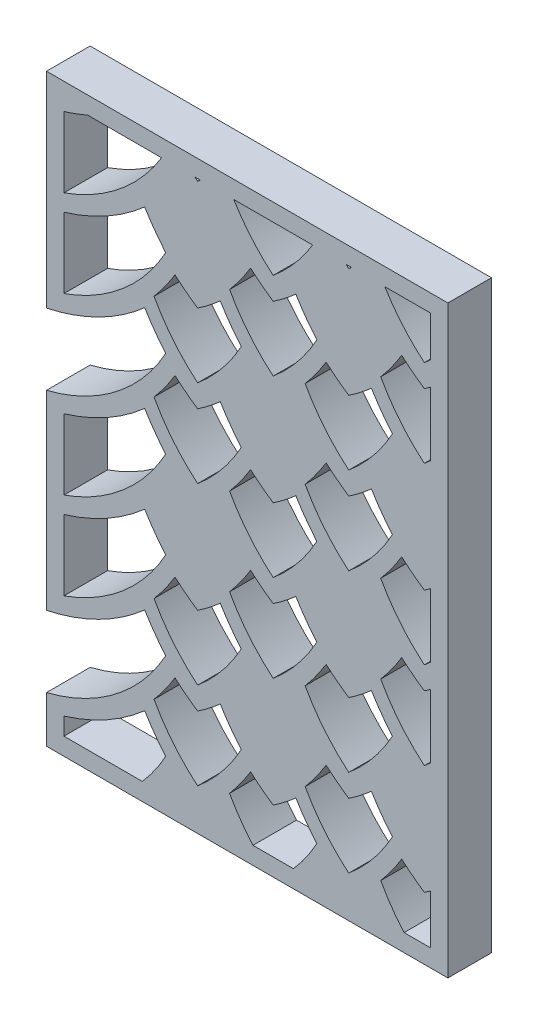
SolidWorks part; units mm, degrees
ref_plane "Front Plane" through (0, 0, 0) normal (0, 0, 1) x (1, 0, 0)
ref_plane "Top Plane" through (0, 0, 0) normal (0, 1, 0) x (1, 0, 0)
ref_plane "Right Plane" through (0, 0, 0) normal (1, 0, 0) x (0, 0, -1)
sketch "Sketch2" plane through (0, 0, 0) normal (0, 0, 1) x (1, 0, 0)
  line L0 (0, -12.607) -> (0, 160.3809) construction
  arc A12 (17.3205, 5.288) -> (12.3204, 11.3793) centre (31.1051, 21.7008) cw
  arc A13 (12.3204, 11.3793) -> (14.7264, 14.712) centre (-6.459, 27.4714) ccw
  arc A14 (17.3205, 12.7089) -> (14.7264, 14.712) centre (31.1051, 33.242) cw
  arc A15 (17.3205, 12.7089) -> (19.9146, 14.712) centre (3.5359, 33.242) ccw
  arc A16 (22.3206, 11.3793) -> (19.9146, 14.712) centre (41.1, 27.4714) cw
  arc A17 (17.3205, 5.288) -> (22.3206, 11.3793) centre (3.5359, 21.7008) ccw
  arc A18 (25.9808, 10.288) -> (20.9807, 16.3793) centre (39.7653, 26.7008) cw
  arc A19 (20.9807, 16.3793) -> (23.3866, 19.712) centre (2.2013, 32.4714) ccw
  arc A20 (25.9808, 17.7089) -> (23.3866, 19.712) centre (39.7653, 38.242) cw
  arc A21 (25.9808, 17.7089) -> (28.5749, 19.712) centre (12.1962, 38.242) ccw
  arc A22 (30.9808, 16.3793) -> (28.5749, 19.712) centre (49.7603, 32.4714) cw
  arc A23 (25.9808, 10.288) -> (30.9808, 16.3793) centre (12.1962, 26.7008) ccw
  arc A30 (43.3013, 20.288) -> (38.3012, 26.3793) centre (57.0859, 36.7008) cw
  arc A31 (38.3012, 26.3793) -> (40.7071, 29.712) centre (19.5218, 42.4714) ccw
  arc A32 (43.3013, 27.7089) -> (40.7071, 29.712) centre (57.0859, 48.242) cw
  arc A33 (43.3013, 27.7089) -> (45.8954, 29.712) centre (29.5167, 48.242) ccw
  arc A34 (48.3013, 26.3793) -> (45.8954, 29.712) centre (67.0808, 42.4714) cw
  arc A35 (43.3013, 20.288) -> (48.3013, 26.3793) centre (29.5167, 36.7008) ccw
  arc A36 (51.9615, 25.288) -> (46.9615, 31.3793) centre (65.7461, 41.7008) cw
  arc A37 (46.9615, 31.3793) -> (49.3674, 34.712) centre (28.182, 47.4714) ccw
  arc A38 (51.9615, 32.7089) -> (49.3674, 34.712) centre (65.7461, 53.242) cw
  arc A39 (51.9615, 32.7089) -> (54.5557, 34.712) centre (38.1769, 53.242) ccw
  arc A40 (56.9616, 31.3793) -> (54.5557, 34.712) centre (75.741, 47.4714) cw
  arc A41 (51.9615, 25.288) -> (56.9616, 31.3793) centre (38.1769, 41.7008) ccw
  arc A60 (25.9808, 20.288) -> (20.9807, 26.3793) centre (39.7653, 36.7008) cw
  arc A61 (20.9807, 26.3793) -> (23.3866, 29.712) centre (2.2013, 42.4714) ccw
  arc A62 (25.9808, 27.7089) -> (23.3866, 29.712) centre (39.7653, 48.242) cw
  arc A63 (25.9808, 27.7089) -> (28.5749, 29.712) centre (12.1962, 48.242) ccw
  arc A64 (30.9808, 26.3793) -> (28.5749, 29.712) centre (49.7603, 42.4714) cw
  arc A65 (25.9808, 20.288) -> (30.9808, 26.3793) centre (12.1962, 36.7008) ccw
  arc A66 (34.641, 25.288) -> (29.641, 31.3793) centre (48.4256, 41.7008) cw
  arc A67 (29.641, 31.3793) -> (32.0469, 34.712) centre (10.8615, 47.4714) ccw
  arc A68 (34.641, 32.7089) -> (32.0469, 34.712) centre (48.4256, 53.242) cw
  arc A69 (34.641, 32.7089) -> (37.2351, 34.712) centre (20.8564, 53.242) ccw
  arc A70 (39.6411, 31.3793) -> (37.2351, 34.712) centre (58.4205, 47.4714) cw
  arc A71 (34.641, 25.288) -> (39.6411, 31.3793) centre (20.8564, 41.7008) ccw
  arc A78 (51.9615, 35.288) -> (46.9615, 41.3793) centre (65.7461, 51.7008) cw
  arc A79 (46.9615, 41.3793) -> (49.3674, 44.712) centre (28.182, 57.4714) ccw
  arc A80 (51.9615, 42.7089) -> (49.3674, 44.712) centre (65.7461, 63.242) cw
  arc A81 (51.9615, 42.7089) -> (54.5557, 44.712) centre (38.1769, 63.242) ccw
  arc A82 (56.9616, 41.3793) -> (54.5557, 44.712) centre (75.741, 57.4714) cw
  arc A83 (51.9615, 35.288) -> (56.9616, 41.3793) centre (38.1769, 51.7008) ccw
  arc A84 (60.6218, 40.288) -> (55.6217, 46.3793) centre (74.4064, 56.7008) cw
  arc A85 (55.6217, 46.3793) -> (58.0276, 49.712) centre (36.8423, 62.4714) ccw
  arc A86 (60.6218, 47.7089) -> (58.0276, 49.712) centre (74.4064, 68.242) cw
  arc A87 (60.6218, 47.7089) -> (63.2159, 49.712) centre (46.8372, 68.242) ccw
  arc A88 (65.6218, 46.3793) -> (63.2159, 49.712) centre (84.4013, 62.4714) cw
  arc A89 (60.6218, 40.288) -> (65.6218, 46.3793) centre (46.8372, 56.7008) ccw
  arc A96 (17.3205, 25.288) -> (12.3204, 31.3793) centre (31.1051, 41.7008) cw
  arc A97 (12.3204, 31.3793) -> (14.7264, 34.712) centre (-6.459, 47.4714) ccw
  arc A98 (17.3205, 32.7089) -> (14.7264, 34.712) centre (31.1051, 53.242) cw
  arc A99 (17.3205, 32.7089) -> (19.9146, 34.712) centre (3.5359, 53.242) ccw
  arc A100 (22.3206, 31.3793) -> (19.9146, 34.712) centre (41.1, 47.4714) cw
  arc A101 (17.3205, 25.288) -> (22.3206, 31.3793) centre (3.5359, 41.7008) ccw
  arc A108 (34.641, 35.288) -> (29.641, 41.3793) centre (48.4256, 51.7008) cw
  arc A109 (29.641, 41.3793) -> (32.0469, 44.712) centre (10.8615, 57.4714) ccw
  arc A110 (34.641, 42.7089) -> (32.0469, 44.712) centre (48.4256, 63.242) cw
  arc A111 (34.641, 42.7089) -> (37.2351, 44.712) centre (20.8564, 63.242) ccw
  arc A112 (39.6411, 41.3793) -> (37.2351, 44.712) centre (58.4205, 57.4714) cw
  arc A113 (34.641, 35.288) -> (39.6411, 41.3793) centre (20.8564, 51.7008) ccw
  arc A114 (43.3013, 40.288) -> (38.3012, 46.3793) centre (57.0859, 56.7008) cw
  arc A115 (38.3012, 46.3793) -> (40.7071, 49.712) centre (19.5218, 62.4714) ccw
  arc A116 (43.3013, 47.7089) -> (40.7071, 49.712) centre (57.0859, 68.242) cw
  arc A117 (43.3013, 47.7089) -> (45.8954, 49.712) centre (29.5167, 68.242) ccw
  arc A118 (48.3013, 46.3793) -> (45.8954, 49.712) centre (67.0808, 62.4714) cw
  arc A119 (43.3013, 40.288) -> (48.3013, 46.3793) centre (29.5167, 56.7008) ccw
  arc A126 (60.6218, 50.288) -> (55.6217, 56.3793) centre (74.4064, 66.7008) cw
  arc A127 (55.6217, 56.3793) -> (58.0276, 59.712) centre (36.8423, 72.4714) ccw
  arc A128 (60.6218, 57.7089) -> (58.0276, 59.712) centre (74.4064, 78.242) cw
  arc A129 (60.6218, 57.7089) -> (63.2159, 59.712) centre (46.8372, 78.242) ccw
  arc A130 (65.6218, 56.3793) -> (63.2159, 59.712) centre (84.4013, 72.4714) cw
  arc A131 (60.6218, 50.288) -> (65.6218, 56.3793) centre (46.8372, 66.7008) ccw
  arc A138 (17.3205, 35.288) -> (12.3204, 41.3793) centre (31.1051, 51.7008) cw
  arc A139 (12.3204, 41.3793) -> (14.7264, 44.712) centre (-6.459, 57.4714) ccw
  arc A140 (17.3205, 42.7089) -> (14.7264, 44.712) centre (31.1051, 63.242) cw
  arc A141 (17.3205, 42.7089) -> (19.9146, 44.712) centre (3.5359, 63.242) ccw
  arc A142 (22.3206, 41.3793) -> (19.9146, 44.712) centre (41.1, 57.4714) cw
  arc A143 (17.3205, 35.288) -> (22.3206, 41.3793) centre (3.5359, 51.7008) ccw
  arc A144 (25.9808, 40.288) -> (20.9807, 46.3793) centre (39.7653, 56.7008) cw
  arc A145 (20.9807, 46.3793) -> (23.3866, 49.712) centre (2.2013, 62.4714) ccw
  arc A146 (25.9808, 47.7089) -> (23.3866, 49.712) centre (39.7653, 68.242) cw
  arc A147 (25.9808, 47.7089) -> (28.5749, 49.712) centre (12.1962, 68.242) ccw
  arc A148 (30.9808, 46.3793) -> (28.5749, 49.712) centre (49.7603, 62.4714) cw
  arc A149 (25.9808, 40.288) -> (30.9808, 46.3793) centre (12.1962, 56.7008) ccw
  arc A156 (43.3013, 50.288) -> (38.3012, 56.3793) centre (57.0859, 66.7008) cw
  arc A157 (38.3012, 56.3793) -> (40.7071, 59.712) centre (19.5218, 72.4714) ccw
  arc A158 (43.3013, 57.7089) -> (40.7071, 59.712) centre (57.0859, 78.242) cw
  arc A159 (43.3013, 57.7089) -> (45.8954, 59.712) centre (29.5167, 78.242) ccw
  arc A160 (48.3013, 56.3793) -> (45.8954, 59.712) centre (67.0808, 72.4714) cw
  arc A161 (43.3013, 50.288) -> (48.3013, 56.3793) centre (29.5167, 66.7008) ccw
  arc A162 (51.9615, 55.288) -> (46.9615, 61.3793) centre (65.7461, 71.7008) cw
  arc A163 (46.9615, 61.3793) -> (49.3674, 64.712) centre (28.182, 77.4714) ccw
  arc A164 (51.9615, 62.7089) -> (49.3674, 64.712) centre (65.7461, 83.242) cw
  arc A165 (51.9615, 62.7089) -> (54.5557, 64.712) centre (38.1769, 83.242) ccw
  arc A166 (56.9616, 61.3793) -> (54.5557, 64.712) centre (75.741, 77.4714) cw
  arc A167 (51.9615, 55.288) -> (56.9616, 61.3793) centre (38.1769, 71.7008) ccw
  arc A186 (25.9808, 50.288) -> (20.9807, 56.3793) centre (39.7653, 66.7008) cw
  arc A187 (20.9807, 56.3793) -> (23.3866, 59.712) centre (2.2013, 72.4714) ccw
  arc A188 (25.9808, 57.7089) -> (23.3866, 59.712) centre (39.7653, 78.242) cw
  arc A189 (25.9808, 57.7089) -> (28.5749, 59.712) centre (12.1962, 78.242) ccw
  arc A190 (30.9808, 56.3793) -> (28.5749, 59.712) centre (49.7603, 72.4714) cw
  arc A191 (25.9808, 50.288) -> (30.9808, 56.3793) centre (12.1962, 66.7008) ccw
  arc A192 (34.641, 55.288) -> (29.641, 61.3793) centre (48.4256, 71.7008) cw
  arc A193 (29.641, 61.3793) -> (32.0469, 64.712) centre (10.8615, 77.4714) ccw
  arc A194 (34.641, 62.7089) -> (32.0469, 64.712) centre (48.4256, 83.242) cw
  arc A195 (34.641, 62.7089) -> (37.2351, 64.712) centre (20.8564, 83.242) ccw
  arc A196 (39.6411, 61.3793) -> (37.2351, 64.712) centre (58.4205, 77.4714) cw
  arc A197 (34.641, 55.288) -> (39.6411, 61.3793) centre (20.8564, 71.7008) ccw
  arc A204 (51.9615, 65.288) -> (46.9615, 71.3793) centre (65.7461, 81.7008) cw
  arc A205 (46.9615, 71.3793) -> (49.3674, 74.712) centre (28.182, 87.4714) ccw
  arc A206 (51.9615, 72.7089) -> (49.3674, 74.712) centre (65.7461, 93.242) cw
  arc A207 (51.9615, 72.7089) -> (54.5557, 74.712) centre (38.1769, 93.242) ccw
  arc A208 (56.9616, 71.3793) -> (54.5557, 74.712) centre (75.741, 87.4714) cw
  arc A209 (51.9615, 65.288) -> (56.9616, 71.3793) centre (38.1769, 81.7008) ccw
  arc A210 (60.6218, 70.288) -> (55.6217, 76.3793) centre (74.4064, 86.7008) cw
  arc A211 (55.6217, 76.3793) -> (58.0276, 79.712) centre (36.8423, 92.4714) ccw
  arc A212 (60.6218, 77.7089) -> (58.0276, 79.712) centre (74.4064, 98.242) cw
  arc A213 (60.6218, 77.7089) -> (63.2159, 79.712) centre (46.8372, 98.242) ccw
  arc A214 (65.6218, 76.3793) -> (63.2159, 79.712) centre (84.4013, 92.4714) cw
  arc A215 (60.6218, 70.288) -> (65.6218, 76.3793) centre (46.8372, 86.7008) ccw
  arc A222 (17.3205, 55.288) -> (12.3204, 61.3793) centre (31.1051, 71.7008) cw
  arc A223 (12.3204, 61.3793) -> (14.7264, 64.712) centre (-6.459, 77.4714) ccw
  arc A224 (17.3205, 62.7089) -> (14.7264, 64.712) centre (31.1051, 83.242) cw
  arc A225 (17.3205, 62.7089) -> (19.9146, 64.712) centre (3.5359, 83.242) ccw
  arc A226 (22.3206, 61.3793) -> (19.9146, 64.712) centre (41.1, 77.4714) cw
  arc A227 (17.3205, 55.288) -> (22.3206, 61.3793) centre (3.5359, 71.7008) ccw
  arc A234 (34.641, 65.288) -> (29.641, 71.3793) centre (48.4256, 81.7008) cw
  arc A235 (29.641, 71.3793) -> (32.0469, 74.712) centre (10.8615, 87.4714) ccw
  arc A236 (34.641, 72.7089) -> (32.0469, 74.712) centre (48.4256, 93.242) cw
  arc A237 (34.641, 72.7089) -> (37.2351, 74.712) centre (20.8564, 93.242) ccw
  arc A238 (39.6411, 71.3793) -> (37.2351, 74.712) centre (58.4205, 87.4714) cw
  arc A239 (34.641, 65.288) -> (39.6411, 71.3793) centre (20.8564, 81.7008) ccw
  arc A240 (43.3013, 70.288) -> (38.3012, 76.3793) centre (57.0859, 86.7008) cw
  arc A241 (38.3012, 76.3793) -> (40.7071, 79.712) centre (19.5218, 92.4714) ccw
  arc A242 (43.3013, 77.7089) -> (40.7071, 79.712) centre (57.0859, 98.242) cw
  arc A243 (43.3013, 77.7089) -> (45.8954, 79.712) centre (29.5167, 98.242) ccw
  arc A244 (48.3013, 76.3793) -> (45.8954, 79.712) centre (67.0808, 92.4714) cw
  arc A245 (43.3013, 70.288) -> (48.3013, 76.3793) centre (29.5167, 86.7008) ccw
  arc A252 (60.6218, 80.288) -> (55.6217, 86.3793) centre (74.4064, 96.7008) cw
  arc A253 (55.6217, 86.3793) -> (58.0276, 89.712) centre (36.8423, 102.4714) ccw
  arc A254 (60.6218, 87.7089) -> (58.0276, 89.712) centre (74.4064, 108.242) cw
  arc A255 (60.6218, 87.7089) -> (63.2159, 89.712) centre (46.8372, 108.242) ccw
  arc A256 (65.6218, 86.3793) -> (63.2159, 89.712) centre (84.4013, 102.4714) cw
  arc A257 (60.6218, 80.288) -> (65.6218, 86.3793) centre (46.8372, 96.7008) ccw
  arc A264 (17.3205, 65.288) -> (12.3204, 71.3793) centre (31.1051, 81.7008) cw
  arc A265 (12.3204, 71.3793) -> (14.7264, 74.712) centre (-6.459, 87.4714) ccw
  arc A266 (17.3205, 72.7089) -> (14.7264, 74.712) centre (31.1051, 93.242) cw
  arc A267 (17.3205, 72.7089) -> (19.9146, 74.712) centre (3.5359, 93.242) ccw
  arc A268 (22.3206, 71.3793) -> (19.9146, 74.712) centre (41.1, 87.4714) cw
  arc A269 (17.3205, 65.288) -> (22.3206, 71.3793) centre (3.5359, 81.7008) ccw
  arc A270 (25.9808, 70.288) -> (20.9807, 76.3793) centre (39.7653, 86.7008) cw
  arc A271 (20.9807, 76.3793) -> (23.3866, 79.712) centre (2.2013, 92.4714) ccw
  arc A272 (25.9808, 77.7089) -> (23.3866, 79.712) centre (39.7653, 98.242) cw
  arc A273 (25.9808, 77.7089) -> (28.5749, 79.712) centre (12.1962, 98.242) ccw
  arc A274 (30.9808, 76.3793) -> (28.5749, 79.712) centre (49.7603, 92.4714) cw
  arc A275 (25.9808, 70.288) -> (30.9808, 76.3793) centre (12.1962, 86.7008) ccw
  arc A282 (43.3013, 80.288) -> (38.3012, 86.3793) centre (57.0859, 96.7008) cw
  arc A283 (38.3012, 86.3793) -> (40.7071, 89.712) centre (19.5218, 102.4714) ccw
  arc A284 (43.3013, 87.7089) -> (40.7071, 89.712) centre (57.0859, 108.242) cw
  arc A285 (43.3013, 87.7089) -> (45.8954, 89.712) centre (29.5167, 108.242) ccw
  arc A286 (48.3013, 86.3793) -> (45.8954, 89.712) centre (67.0808, 102.4714) cw
  arc A287 (43.3013, 80.288) -> (48.3013, 86.3793) centre (29.5167, 96.7008) ccw
  arc A288 (51.9615, 85.288) -> (46.9615, 91.3793) centre (65.7461, 101.7008) cw
  arc A289 (46.9615, 91.3793) -> (49.3674, 94.712) centre (28.182, 107.4714) ccw
  arc A290 (51.9615, 92.7089) -> (49.3674, 94.712) centre (65.7461, 113.242) cw
  arc A291 (51.9615, 92.7089) -> (54.5557, 94.712) centre (38.1769, 113.242) ccw
  arc A292 (56.9616, 91.3793) -> (54.5557, 94.712) centre (75.741, 107.4714) cw
  arc A293 (51.9615, 85.288) -> (56.9616, 91.3793) centre (38.1769, 101.7008) ccw
  arc A312 (25.9808, 80.288) -> (20.9807, 86.3793) centre (39.7653, 96.7008) cw
  arc A313 (20.9807, 86.3793) -> (23.3866, 89.712) centre (2.2013, 102.4714) ccw
  arc A314 (25.9808, 87.7089) -> (23.3866, 89.712) centre (39.7653, 108.242) cw
  arc A315 (25.9808, 87.7089) -> (28.5749, 89.712) centre (12.1962, 108.242) ccw
  arc A316 (30.9808, 86.3793) -> (28.5749, 89.712) centre (49.7603, 102.4714) cw
  arc A317 (25.9808, 80.288) -> (30.9808, 86.3793) centre (12.1962, 96.7008) ccw
  arc A318 (34.641, 85.288) -> (29.641, 91.3793) centre (48.4256, 101.7008) cw
  arc A319 (29.641, 91.3793) -> (32.0469, 94.712) centre (10.8615, 107.4714) ccw
  arc A320 (34.641, 92.7089) -> (32.0469, 94.712) centre (48.4256, 113.242) cw
  arc A321 (34.641, 92.7089) -> (37.2351, 94.712) centre (20.8564, 113.242) ccw
  arc A322 (39.6411, 91.3793) -> (37.2351, 94.712) centre (58.4205, 107.4714) cw
  arc A323 (34.641, 85.288) -> (39.6411, 91.3793) centre (20.8564, 101.7008) ccw
  arc A330 (51.9615, 95.288) -> (46.9615, 101.3793) centre (65.7461, 111.7008) cw
  arc A331 (46.9615, 101.3793) -> (49.3674, 104.712) centre (28.182, 117.4714) ccw
  arc A332 (51.9615, 102.7089) -> (49.3674, 104.712) centre (65.7461, 123.242) cw
  arc A333 (51.9615, 102.7089) -> (54.5557, 104.712) centre (38.1769, 123.242) ccw
  arc A334 (56.9616, 101.3793) -> (54.5557, 104.712) centre (75.741, 117.4714) cw
  arc A335 (51.9615, 95.288) -> (56.9616, 101.3793) centre (38.1769, 111.7008) ccw
  arc A336 (60.6218, 100.288) -> (55.6217, 106.3793) centre (74.4064, 116.7008) cw
  arc A337 (55.6217, 106.3793) -> (58.0276, 109.712) centre (36.8423, 122.4714) ccw
  arc A338 (60.6218, 107.7089) -> (58.0276, 109.712) centre (74.4064, 128.242) cw
  arc A339 (60.6218, 107.7089) -> (63.2159, 109.712) centre (46.8372, 128.242) ccw
  arc A340 (65.6218, 106.3793) -> (63.2159, 109.712) centre (84.4013, 122.4714) cw
  arc A341 (60.6218, 100.288) -> (65.6218, 106.3793) centre (46.8372, 116.7008) ccw
  arc A396 (17.3205, 85.288) -> (12.3204, 91.3793) centre (31.1051, 101.7008) cw
  arc A397 (12.3204, 91.3793) -> (14.7264, 94.712) centre (-6.459, 107.4714) ccw
  arc A398 (17.3205, 92.7089) -> (14.7264, 94.712) centre (31.1051, 113.242) cw
  arc A399 (17.3205, 92.7089) -> (19.9146, 94.712) centre (3.5359, 113.242) ccw
  arc A400 (22.3206, 91.3793) -> (19.9146, 94.712) centre (41.1, 107.4714) cw
  arc A401 (17.3205, 85.288) -> (22.3206, 91.3793) centre (3.5359, 101.7008) ccw
  arc A408 (34.641, 95.288) -> (29.641, 101.3793) centre (48.4256, 111.7008) cw
  arc A409 (29.641, 101.3793) -> (32.0469, 104.712) centre (10.8615, 117.4714) ccw
  arc A410 (34.641, 102.7089) -> (32.0469, 104.712) centre (48.4256, 123.242) cw
  arc A411 (34.641, 102.7089) -> (37.2351, 104.712) centre (20.8564, 123.242) ccw
  arc A412 (39.6411, 101.3793) -> (37.2351, 104.712) centre (58.4205, 117.4714) cw
  arc A413 (34.641, 95.288) -> (39.6411, 101.3793) centre (20.8564, 111.7008) ccw
  arc A414 (43.3013, 100.288) -> (38.3012, 106.3793) centre (57.0859, 116.7008) cw
  arc A415 (38.3012, 106.3793) -> (40.7071, 109.712) centre (19.5218, 122.4714) ccw
  arc A416 (43.3013, 107.7089) -> (40.7071, 109.712) centre (57.0859, 128.242) cw
  arc A417 (43.3013, 107.7089) -> (45.8954, 109.712) centre (29.5167, 128.242) ccw
  arc A418 (48.3013, 106.3793) -> (45.8954, 109.712) centre (67.0808, 122.4714) cw
  arc A419 (43.3013, 100.288) -> (48.3013, 106.3793) centre (29.5167, 116.7008) ccw
  arc A426 (60.6218, 110.288) -> (55.6217, 116.3793) centre (74.4064, 126.7008) cw
  arc A427 (55.6217, 116.3793) -> (58.0276, 119.712) centre (36.8423, 132.4714) ccw
  arc A428 (60.6218, 117.7089) -> (58.0276, 119.712) centre (74.4064, 138.242) cw
  arc A429 (60.6218, 117.7089) -> (63.2159, 119.712) centre (46.8372, 138.242) ccw
  arc A430 (65.6218, 116.3793) -> (63.2159, 119.712) centre (84.4013, 132.4714) cw
  arc A431 (60.6218, 110.288) -> (65.6218, 116.3793) centre (46.8372, 126.7008) ccw
  arc A435 (8.6603, 97.7089) -> (11.2544, 99.712) centre (-5.1243, 118.242) ccw
  arc A436 (13.6603, 96.3793) -> (11.2544, 99.712) centre (32.4398, 112.4714) cw
  arc A437 (8.6603, 90.288) -> (13.6603, 96.3793) centre (-5.1243, 106.7008) ccw
  arc A438 (17.3205, 95.288) -> (12.3204, 101.3793) centre (31.1051, 111.7008) cw
  arc A439 (12.3204, 101.3793) -> (14.7264, 104.712) centre (-6.459, 117.4714) ccw
  arc A440 (17.3205, 102.7089) -> (14.7264, 104.712) centre (31.1051, 123.242) cw
  arc A441 (17.3205, 102.7089) -> (19.9146, 104.712) centre (3.5359, 123.242) ccw
  arc A442 (22.3206, 101.3793) -> (19.9146, 104.712) centre (41.1, 117.4714) cw
  arc A443 (17.3205, 95.288) -> (22.3206, 101.3793) centre (3.5359, 111.7008) ccw
  arc A444 (25.9808, 100.288) -> (20.9807, 106.3793) centre (39.7653, 116.7008) cw
  arc A445 (20.9807, 106.3793) -> (23.3866, 109.712) centre (2.2013, 122.4714) ccw
  arc A446 (25.9808, 107.7089) -> (23.3866, 109.712) centre (39.7653, 128.242) cw
  arc A447 (25.9808, 107.7089) -> (28.5749, 109.712) centre (12.1962, 128.242) ccw
  arc A448 (30.9808, 106.3793) -> (28.5749, 109.712) centre (49.7603, 122.4714) cw
  arc A449 (25.9808, 100.288) -> (30.9808, 106.3793) centre (12.1962, 116.7008) ccw
  arc A456 (43.3013, 110.288) -> (38.3012, 116.3793) centre (57.0859, 126.7008) cw
  arc A457 (38.3012, 116.3793) -> (40.7071, 119.712) centre (19.5218, 132.4714) ccw
  arc A458 (43.3013, 117.7089) -> (40.7071, 119.712) centre (57.0859, 138.242) cw
  arc A459 (43.3013, 117.7089) -> (45.8954, 119.712) centre (29.5167, 138.242) ccw
  arc A460 (48.3013, 116.3793) -> (45.8954, 119.712) centre (67.0808, 132.4714) cw
  arc A461 (43.3013, 110.288) -> (48.3013, 116.3793) centre (29.5167, 126.7008) ccw
  arc A462 (51.9615, 115.288) -> (46.9615, 121.3793) centre (65.7461, 131.7008) cw
  arc A463 (46.9615, 121.3793) -> (49.3674, 124.712) centre (28.182, 137.4714) ccw
  arc A464 (51.9615, 122.7089) -> (49.3674, 124.712) centre (65.7461, 143.242) cw
  arc A465 (51.9615, 122.7089) -> (54.5557, 124.712) centre (38.1769, 143.242) ccw
  arc A466 (56.9616, 121.3793) -> (54.5557, 124.712) centre (75.741, 137.4714) cw
  arc A467 (51.9615, 115.288) -> (56.9616, 121.3793) centre (38.1769, 131.7008) ccw
  arc A486 (0, 5.288) -> (-5.0001, 11.3793) centre (13.7846, 21.7008) cw
  arc A487 (-5.0001, 11.3793) -> (-2.5941, 14.712) centre (-23.7795, 27.4714) ccw
  arc A488 (0, 12.7089) -> (-2.5941, 14.712) centre (13.7846, 33.242) cw
  arc A489 (0, 12.7089) -> (2.5941, 14.712) centre (-13.7846, 33.242) ccw
  arc A490 (5.0001, 11.3793) -> (2.5941, 14.712) centre (23.7795, 27.4714) cw
  arc A491 (0, 5.288) -> (5.0001, 11.3793) centre (-13.7846, 21.7008) ccw
  arc A540 (8.6603, 97.7089) -> (0, 94.0477) centre (-5.1243, 118.242) cw
  arc A541 (8.6603, 90.288) -> (0, 85.8889) centre (-5.1243, 106.7008) cw
  arc A542 (-13.6603, 96.3793) -> (-11.2544, 99.712) centre (-32.4398, 112.4714) ccw
  arc A543 (-8.6603, 97.7089) -> (-11.2544, 99.712) centre (5.1243, 118.242) cw
  arc A544 (-8.6603, 97.7089) -> (0, 94.0477) centre (5.1243, 118.242) ccw
  arc A545 (-8.6603, 90.288) -> (-13.6603, 96.3793) centre (5.1243, 106.7008) cw
  arc A546 (-8.6603, 90.288) -> (0, 85.8889) centre (5.1243, 106.7008) ccw
  arc A547 (-13.6603, 86.3793) -> (-11.2544, 89.712) centre (-32.4398, 102.4714) ccw
  arc A548 (-8.6603, 87.7089) -> (-11.2544, 89.712) centre (5.1243, 108.242) cw
  arc A549 (-8.6603, 87.7089) -> (0, 84.0477) centre (5.1243, 108.242) ccw
  arc A550 (8.6603, 87.7089) -> (0, 84.0477) centre (-5.1243, 108.242) cw
  arc A551 (8.6603, 87.7089) -> (11.2544, 89.712) centre (-5.1243, 108.242) ccw
  arc A552 (13.6603, 86.3793) -> (11.2544, 89.712) centre (32.4398, 102.4714) cw
  arc A553 (8.6603, 80.288) -> (13.6603, 86.3793) centre (-5.1243, 96.7008) ccw
  arc A554 (8.6603, 80.288) -> (0, 75.8889) centre (-5.1243, 96.7008) cw
  arc A555 (-8.6603, 80.288) -> (0, 75.8889) centre (5.1243, 96.7008) ccw
  arc A556 (-8.6603, 80.288) -> (-13.6603, 86.3793) centre (5.1243, 96.7008) cw
  arc A557 (-13.6603, 76.3793) -> (-11.2544, 79.712) centre (-32.4398, 92.4714) ccw
  arc A558 (-8.6603, 77.7089) -> (-11.2544, 79.712) centre (5.1243, 98.242) cw
  arc A559 (-8.6603, 77.7089) -> (0, 74.0477) centre (5.1243, 98.242) ccw
  arc A560 (8.6603, 77.7089) -> (0, 74.0477) centre (-5.1243, 98.242) cw
  arc A561 (8.6603, 77.7089) -> (11.2544, 79.712) centre (-5.1243, 98.242) ccw
  arc A562 (13.6603, 76.3793) -> (11.2544, 79.712) centre (32.4398, 92.4714) cw
  arc A563 (8.6603, 70.288) -> (13.6603, 76.3793) centre (-5.1243, 86.7008) ccw
  arc A564 (8.6603, 70.288) -> (0, 65.8889) centre (-5.1243, 86.7008) cw
  arc A565 (-8.6603, 70.288) -> (0, 65.8889) centre (5.1243, 86.7008) ccw
  arc A566 (-8.6603, 70.288) -> (-13.6603, 76.3793) centre (5.1243, 86.7008) cw
  arc A567 (-13.6603, 66.3793) -> (-11.2544, 69.712) centre (-32.4398, 82.4714) ccw
  arc A568 (-8.6603, 67.7089) -> (-11.2544, 69.712) centre (5.1243, 88.242) cw
  arc A569 (-8.6603, 67.7089) -> (0, 64.0477) centre (5.1243, 88.242) ccw
  arc A570 (8.6603, 67.7089) -> (0, 64.0477) centre (-5.1243, 88.242) cw
  arc A571 (8.6603, 67.7089) -> (11.2544, 69.712) centre (-5.1243, 88.242) ccw
  arc A572 (13.6603, 66.3793) -> (11.2544, 69.712) centre (32.4398, 82.4714) cw
  arc A573 (8.6603, 60.288) -> (13.6603, 66.3793) centre (-5.1243, 76.7008) ccw
  arc A574 (8.6603, 60.288) -> (0, 55.8889) centre (-5.1243, 76.7008) cw
  arc A575 (-8.6603, 60.288) -> (0, 55.8889) centre (5.1243, 76.7008) ccw
  arc A576 (-8.6603, 60.288) -> (-13.6603, 66.3793) centre (5.1243, 76.7008) cw
  arc A577 (-13.6603, 56.3793) -> (-11.2544, 59.712) centre (-32.4398, 72.4714) ccw
  arc A578 (-8.6603, 57.7089) -> (-11.2544, 59.712) centre (5.1243, 78.242) cw
  arc A579 (-8.6603, 57.7089) -> (0, 54.0477) centre (5.1243, 78.242) ccw
  arc A580 (8.6603, 57.7089) -> (0, 54.0477) centre (-5.1243, 78.242) cw
  arc A581 (8.6603, 57.7089) -> (11.2544, 59.712) centre (-5.1243, 78.242) ccw
  arc A582 (13.6603, 56.3793) -> (11.2544, 59.712) centre (32.4398, 72.4714) cw
  arc A583 (8.6603, 50.288) -> (13.6603, 56.3793) centre (-5.1243, 66.7008) ccw
  arc A584 (8.6603, 50.288) -> (0, 45.8889) centre (-5.1243, 66.7008) cw
  arc A585 (-8.6603, 50.288) -> (0, 45.8889) centre (5.1243, 66.7008) ccw
  arc A586 (-8.6603, 50.288) -> (-13.6603, 56.3793) centre (5.1243, 66.7008) cw
  arc A587 (-13.6603, 46.3793) -> (-11.2544, 49.712) centre (-32.4398, 62.4714) ccw
  arc A588 (-8.6603, 47.7089) -> (-11.2544, 49.712) centre (5.1243, 68.242) cw
  arc A589 (-8.6603, 47.7089) -> (0, 44.0477) centre (5.1243, 68.242) ccw
  arc A590 (8.6603, 47.7089) -> (0, 44.0477) centre (-5.1243, 68.242) cw
  arc A591 (8.6603, 47.7089) -> (11.2544, 49.712) centre (-5.1243, 68.242) ccw
  arc A592 (13.6603, 46.3793) -> (11.2544, 49.712) centre (32.4398, 62.4714) cw
  arc A593 (8.6603, 40.288) -> (13.6603, 46.3793) centre (-5.1243, 56.7008) ccw
  arc A594 (8.6603, 40.288) -> (0, 35.8889) centre (-5.1243, 56.7008) cw
  arc A595 (-8.6603, 40.288) -> (0, 35.8889) centre (5.1243, 56.7008) ccw
  arc A596 (-8.6603, 40.288) -> (-13.6603, 46.3793) centre (5.1243, 56.7008) cw
  arc A597 (-13.6603, 36.3793) -> (-11.2544, 39.712) centre (-32.4398, 52.4714) ccw
  arc A598 (-8.6603, 37.7089) -> (-11.2544, 39.712) centre (5.1243, 58.242) cw
  arc A599 (-8.6603, 37.7089) -> (0, 34.0477) centre (5.1243, 58.242) ccw
  arc A600 (8.6603, 37.7089) -> (0, 34.0477) centre (-5.1243, 58.242) cw
  arc A601 (8.6603, 37.7089) -> (11.2544, 39.712) centre (-5.1243, 58.242) ccw
  arc A602 (13.6603, 36.3793) -> (11.2544, 39.712) centre (32.4398, 52.4714) cw
  arc A603 (8.6603, 30.288) -> (13.6603, 36.3793) centre (-5.1243, 46.7008) ccw
  arc A604 (8.6603, 30.288) -> (0, 25.8889) centre (-5.1243, 46.7008) cw
  arc A605 (-8.6603, 30.288) -> (0, 25.8889) centre (5.1243, 46.7008) ccw
  arc A606 (-8.6603, 30.288) -> (-13.6603, 36.3793) centre (5.1243, 46.7008) cw
  arc A607 (-13.6603, 26.3793) -> (-11.2544, 29.712) centre (-32.4398, 42.4714) ccw
  arc A608 (-8.6603, 27.7089) -> (-11.2544, 29.712) centre (5.1243, 48.242) cw
  arc A609 (-8.6603, 27.7089) -> (0, 24.0477) centre (5.1243, 48.242) ccw
  arc A610 (8.6603, 27.7089) -> (0, 24.0477) centre (-5.1243, 48.242) cw
  arc A611 (8.6603, 27.7089) -> (11.2544, 29.712) centre (-5.1243, 48.242) ccw
  arc A612 (13.6603, 26.3793) -> (11.2544, 29.712) centre (32.4398, 42.4714) cw
  arc A613 (8.6603, 20.288) -> (13.6603, 26.3793) centre (-5.1243, 36.7008) ccw
  arc A614 (8.6603, 20.288) -> (0, 15.8889) centre (-5.1243, 36.7008) cw
  arc A615 (-8.6603, 20.288) -> (0, 15.8889) centre (5.1243, 36.7008) ccw
  arc A616 (-8.6603, 20.288) -> (-13.6603, 26.3793) centre (5.1243, 36.7008) cw
  point P2 (0, 0)
  point P50 (0, 0)
  dimension "D1" = 8
sketch "Sketch3" plane through (0, 0, 0) normal (0, 0, 1) x (1, 0, 0)
  line L0 (0, -2.3579) -> (0, 7.3299) construction
  line L2 (0, 85.5576) -> (44, 85.5576)
  line L3 (0, 85.5576) -> (0, 22.5576)
  line L4 (0, 22.5576) -> (44, 22.5576)
  line L5 (44, 85.5576) -> (44, 22.5576)
  dimension "D1" = 44
  dimension "D2" = 63
extrude "Boss-Extrude1" add sketch "Sketch3" along normal blind 5
sketch "Sketch4" plane through (0, 0, 0) normal (0, 0, 1) x (1, 0, 0)
  line L1 (0, 85.5576) -> (44, 85.5576)
  line L2 (0, 85.5576) -> (0, 22.5576)
  line L3 (0, 22.5576) -> (44, 22.5576)
  line L4 (44, 85.5576) -> (44, 22.5576)
  line L5 (0, 85.5576) -> (46, 85.5576)
  line L6 (0, 85.5576) -> (0, 87.5576)
  line L7 (0, 87.5576) -> (46, 87.5576)
  line L8 (46, 85.5576) -> (46, 87.5576)
  line L9 (46, 85.5576) -> (44, 85.5576)
  line L10 (46, 85.5576) -> (46, 20.5576)
  line L11 (46, 20.5576) -> (44, 20.5576)
  line L12 (44, 85.5576) -> (44, 20.5576)
  line L13 (44, 20.5576) -> (0, 20.5576)
  line L14 (44, 20.5576) -> (44, 22.5576)
  line L15 (44, 22.5576) -> (0, 22.5576)
  line L16 (0, 20.5576) -> (0, 22.5576)
  dimension "D1" = 2
  dimension "D2" = 2
  dimension "D3" = 2
extrude "Cut-Extrude2" cut sketch "Sketch2" along normal through all
extrude "Boss-Extrude2" add sketch "Sketch4" along normal blind 5 contours L16 L13 L12 L3 | L4 L12 L11 L10 L5 | L5 L8 L7 L6 L1
sketch "Sketch5" plane through (0, 0, 0) normal (0, 0, 1) x (1, 0, 0)
  line L0 (0, 20.5576) -> (0, 22.5576) construction
  line L1 (0, 21.5576) -> (2, 21.5576)
  line L2 (0, 21.5576) -> (0, 25.2057)
  line L3 (0, 25.2057) -> (2, 25.2057)
  line L4 (2, 21.5576) -> (2, 25.2057)
  line L6 (0, 35.8889) -> (2, 35.8889)
  line L7 (0, 35.8889) -> (0, 55.2099)
  line L8 (0, 55.2099) -> (2, 55.2099)
  line L9 (2, 35.8889) -> (2, 55.2099)
  line L18 (0, 65.8889) -> (2, 65.8889)
  line L19 (0, 65.8889) -> (0, 85.929)
  line L20 (0, 85.929) -> (2, 85.929)
  line L21 (2, 65.8889) -> (2, 85.929)
  point P6 (2, 23.3817)
  dimension "D1" = 2
extrude "Boss-Extrude3" add sketch "Sketch5" along normal blind 5
